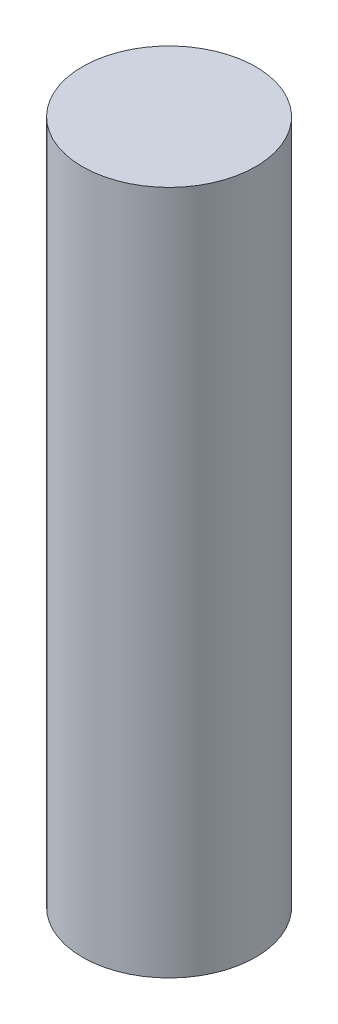
SolidWorks part; units mm, degrees
ref_plane "Front Plane" through (0, 0, 0) normal (0, 0, 1) x (1, 0, 0)
ref_plane "Top Plane" through (0, 0, 0) normal (0, 1, 0) x (1, 0, 0)
ref_plane "Right Plane" through (0, 0, 0) normal (1, 0, 0) x (0, 0, -1)
sketch "Sketch1" plane through (0, 0, 0) normal (0, 1, 0) x (1, 0, 0)
  circle A0 centre (0, 0) radius 9
  dimension "D1" = 18
extrude "Boss-Extrude1" add sketch "Sketch1" along normal blind 71.12
